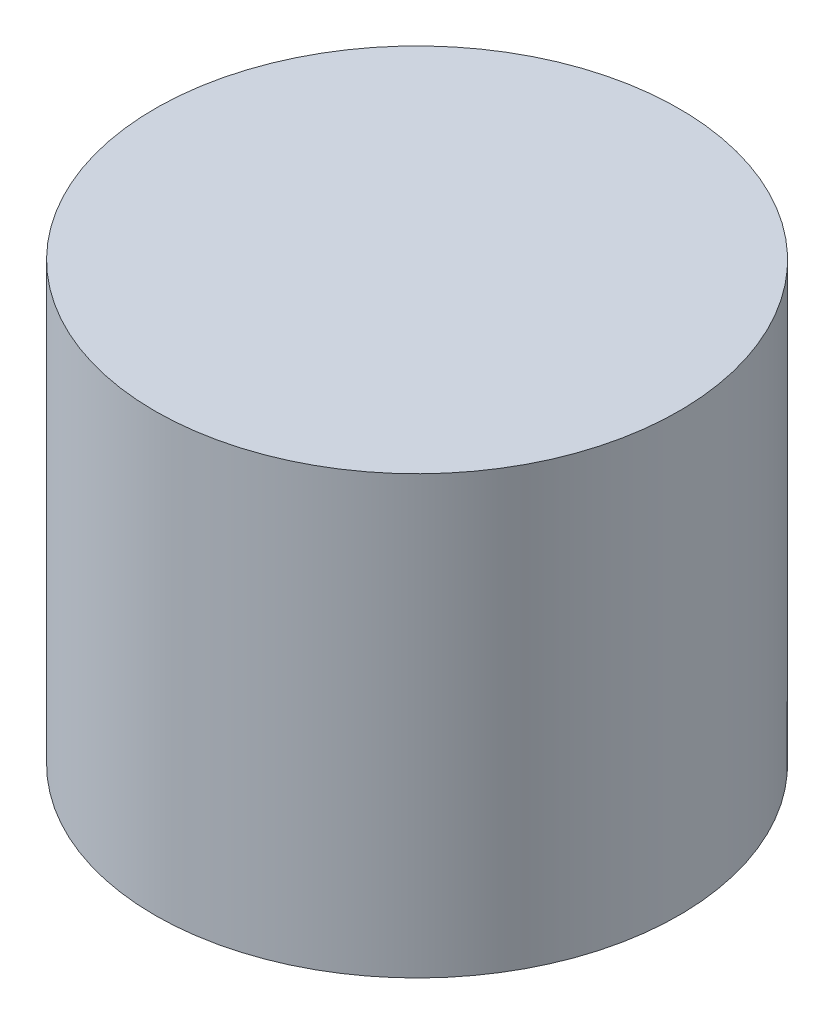
SolidWorks part; units mm, degrees
material "Pure Lead"
ref_plane "Front Plane" through (0, 0, 0) normal (0, 0, 1) x (1, 0, 0)
ref_plane "Top Plane" through (0, 0, 0) normal (0, 1, 0) x (1, 0, 0)
ref_plane "Right Plane" through (0, 0, 0) normal (1, 0, 0) x (0, 0, -1)
sketch "Sketch1" plane through (0, 0, 0) normal (0, 1, 0) x (1, 0, 0)
  circle A0 centre (0, 0) radius 15
  dimension "D1" = 15
extrude "Boss-Extrude1" add sketch "Sketch1" along normal blind 25
